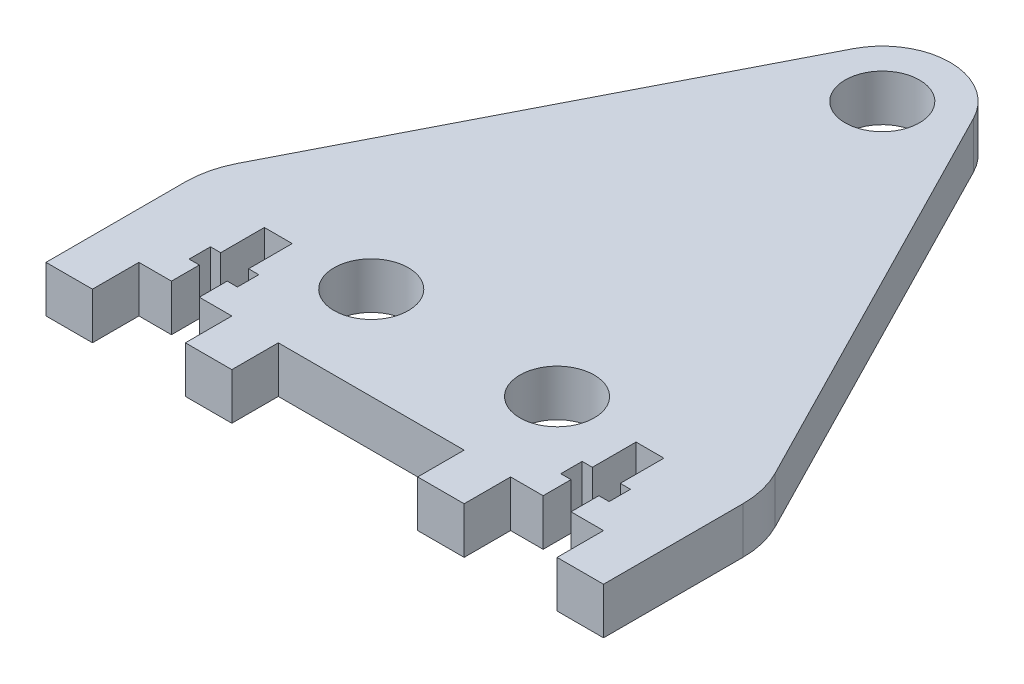
SolidWorks part; units mm, degrees
ref_plane "Front Plane" through (0, 0, 0) normal (0, 0, 1) x (1, 0, 0)
ref_plane "Top Plane" through (0, 0, 0) normal (0, 1, 0) x (1, 0, 0)
ref_plane "Right Plane" through (0, 0, 0) normal (1, 0, 0) x (0, 0, -1)
sketch "Sketch1" plane through (0, 0, 0) normal (0, 1, 0) x (1, 0, 0)
  line L1 (-30, 10) -> (-30, -5)
  line L2 (-30, -5) -> (-25, -5)
  line L3 (-10, -5) -> (-10, 0)
  line L4 (-10, 0) -> (10, 0)
  line L5 (10, -5) -> (10, 0)
  line L6 (30, -5) -> (25, -5)
  line L7 (30, 10) -> (30, -5)
  line L11 (0, 0) -> (0, 43.6328) construction
  line L13 (-28.9011, 14.5574) -> (-6.4922, 58.3241)
  line L14 (6.4922, 58.3241) -> (28.9011, 14.5574)
  line L36 (-25, -5) -> (-25, 0)
  line L37 (-25, 0) -> (-21.5, 0)
  line L38 (-21.5, 0) -> (-21.5, 3)
  line L39 (-21.5, 3) -> (-22.6, 3)
  line L40 (-22.6, 3) -> (-22.6, 5.3)
  line L41 (-22.6, 5.3) -> (-21.5, 5.3)
  line L42 (-21.5, 5.3) -> (-21.5, 10)
  line L43 (-21.5, 10) -> (-18.5, 10)
  line L44 (-18.5, 10) -> (-18.5, 5.3)
  line L45 (-18.5, 5.3) -> (-17.4, 5.3)
  line L46 (-17.4, 5.3) -> (-17.4, 3)
  line L47 (-17.4, 3) -> (-18.5, 3)
  line L48 (-18.5, 3) -> (-18.5, 0)
  line L49 (-18.5, 0) -> (-15, 0)
  line L50 (-15, 0) -> (-15, -5)
  line L51 (-15, -5) -> (-10, -5)
  line L52 (25, 0) -> (21.5, 0)
  line L53 (21.5, 0) -> (21.5, 3)
  line L54 (21.5, 3) -> (22.6, 3)
  line L55 (22.6, 5.3) -> (21.5, 5.3)
  line L56 (22.6, 3) -> (22.6, 5.3)
  line L57 (21.5, 5.3) -> (21.5, 10)
  line L58 (21.5, 10) -> (18.5, 10)
  line L59 (18.5, 10) -> (18.5, 5.3)
  line L60 (18.5, 5.3) -> (17.4, 5.3)
  line L61 (17.4, 5.3) -> (17.4, 3)
  line L62 (17.4, 3) -> (18.5, 3)
  line L63 (18.5, 3) -> (18.5, 0)
  line L64 (18.5, 0) -> (15, 0)
  line L65 (15, 0) -> (15, -5)
  line L66 (25, -5) -> (25, 0)
  line L67 (15, -5) -> (10, -5)
  arc A0 (-6.4922, 58.3241) -> (6.4922, 58.3241) centre (0, 55) cw
  circle A2 centre (0, 55) radius 4
  arc A3 (30, 10) -> (28.9011, 14.5574) centre (20, 10) ccw
  arc A4 (-30, 10) -> (-28.9011, 14.5574) centre (-20, 10) cw
  circle A5 centre (-10, 10) radius 4
  circle A6 centre (10, 10) radius 4
  point P68 (-16.75, 0)
  point P72 (-17.95, 3)
  point P73 (-22.05, 5.3)
  point P74 (-22.05, 3)
  point P78 (22.05, 3)
  point P80 (22.05, 5.3)
  point P88 (17.95, 3)
  point P91 (16.75, 0)
  dimension "D1" = 4
  dimension "D4" = 10
  dimension "D6" = 60
  dimension "D2" = 5
  dimension "D3" = 55
  dimension "D5" = 10
  dimension "D7" = 10
  dimension "D12" = 5
  dimension "D13" = 5
  dimension "D15" = 2.3
  dimension "D16" = 3
  dimension "D17" = 10
  dimension "D18" = 3
  dimension "D19" = 3.5
  dimension "D20" = 5.2
  dimension "D21" = 2.6
  dimension "D22" = 10
  dimension "D23" = 10
extrude "Boss-Extrude1" add sketch "Sketch1" along normal blind 5
